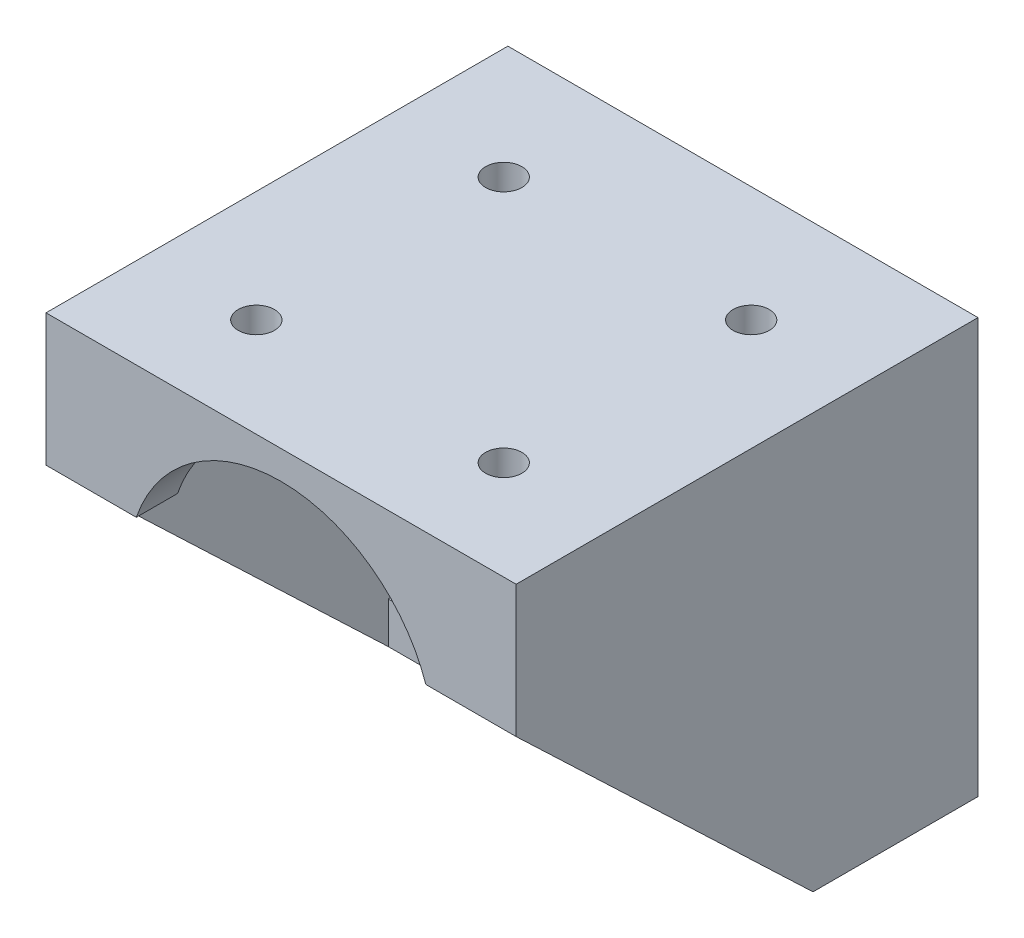
SolidWorks part; units mm, degrees
ref_plane "Plan de face" through (0, 0, 0) normal (0, 0, 1) x (1, 0, 0)
ref_plane "Plan de dessus" through (0, 0, 0) normal (0, 1, 0) x (1, 0, 0)
ref_plane "Plan de droite" through (0, 0, 0) normal (1, 0, 0) x (0, 0, -1)
sketch "Esquisse1" plane through (0, 0, 0) normal (0, 1, 0) x (1, 0, 0)
  line L1 (-23, 23.5) -> (23, 23.5)
  line L2 (-23, 23.5) -> (-23, -23.5)
  line L3 (-23, -23.5) -> (23, -23.5)
  line L4 (23, 23.5) -> (23, -23.5)
  line L5 (-23, 23.5) -> (23, -23.5) construction
  line L6 (-23, -23.5) -> (23, 23.5) construction
  line L7 (-15, 13.5) -> (15, 13.5) construction
  line L8 (-15, 13.5) -> (-15, -16.5) construction
  line L9 (-15, -16.5) -> (15, -16.5) construction
  line L10 (15, 13.5) -> (15, -16.5) construction
  line L11 (-15, 13.5) -> (15, -16.5) construction
  line L12 (-15, -16.5) -> (15, 13.5) construction
  circle A0 centre (-15, 13.5) radius 2.2
  circle A1 centre (-15, -16.5) radius 2.2
  circle A2 centre (15, -16.5) radius 2.2
  circle A3 centre (15, 13.5) radius 2.2
  point P0 (0, 0)
  point P6 (0, -1.5)
  dimension "D6" = 4.4
  dimension "D1" = 46
  dimension "D2" = 47
  dimension "D3" = 7
  dimension "D4" = 8
  dimension "D5" = 30
extrude "Boss.-Extru.1" add sketch "Esquisse1" along normal blind 5
sketch "Esquisse2" plane through (0, 0, 0) normal (0, -1, 0) x (1, 0, 0)
  line L0 (-28.5, -27.5) -> (-28.5, 23.5)
  line L2 (23, -23.5) -> (23, 23.5)
  line L3 (23, 23.5) -> (28.5, 23.5)
  line L6 (-23, -23.5) -> (-23, 23.5)
  line L7 (-23, 23.5) -> (-28.5, 23.5)
  line L9 (23, -23.5) -> (-23, -23.5)
  line L11 (28.5, -27.5) -> (-28.5, -27.5)
  line L13 (28.5, 23.5) -> (28.5, -27.5)
  line L14 (-23, 23.5) -> (23, 23.5) construction
  point P3 (0, -27.5)
  point P8 (0, -23.5)
  dimension "D1" = 57
  dimension "D2" = 51
extrude "Boss.-Extru.2" add sketch "Esquisse2" along normal blind 45.3 from offset 5 offset against normal yes
sketch "Esquisse3" plane through (0, 0, -23.5) normal (0, 0, 1) x (1, 0, 0)
  line L0 (23, 0) -> (-23, 0) construction
  circle A0 centre (0, -10) radius 6.5
  circle A1 centre (0, -17) radius 15.5 construction
  circle A2 centre (7.75, -30.4234) radius 1.6
  circle A3 centre (-7.75, -30.4234) radius 1.6
  circle A4 centre (-15.5, -17) radius 1.6
  circle A5 centre (-7.75, -3.5766) radius 1.6
  circle A6 centre (7.75, -3.5766) radius 1.6
  circle A7 centre (15.5, -17) radius 1.6
  point P22 (0, -17)
  dimension "D2" = 13
  dimension "D4" = 31
  dimension "D5" = 3.2
  dimension "D1" = 10
  dimension "D3" = 17
  dimension "D6" = 6
extrude "Enlèv. mat.-Extru.1" cut sketch "Esquisse3" against normal blind 15
sketch "Esquisse4" plane through (0, 0, -27.5) normal (0, 0, -1) x (-1, 0, 0)
  line L0 (28.5, -40.3) -> (28.5, 5) construction
  line L1 (-28.5, -40.3) -> (28.5, -40.3)
  line L2 (-28.5, -40.3) -> (-28.5, -45.3)
  line L3 (-28.5, -45.3) -> (28.5, -45.3)
  line L4 (28.5, -40.3) -> (28.5, -45.3)
  dimension "D1" = 5
extrude "Boss.-Extru.3" add sketch "Esquisse4" against normal blind 20
sketch "Esquisse7" plane through (0, 5, 0) normal (0, 1, 0) x (1, 0, 0)
  line L0 (28.5, 27.5) -> (28.5, -23.5) construction
  line L1 (-28.5, -23.5) -> (28.5, -23.5)
  line L2 (-28.5, -23.5) -> (-28.5, -28.5)
  line L3 (-28.5, -28.5) -> (28.5, -28.5)
  line L4 (28.5, -23.5) -> (28.5, -28.5)
  dimension "D1" = 5
extrude "Boss.-Extru.4" add sketch "Esquisse7" against normal blind 16
sketch "Esquisse8" plane through (0, 0, 28.5) normal (0, 0, 1) x (1, 0, 0)
  line L0 (-28.5, 5) -> (28.5, 5) construction
  circle A0 centre (0, -17) radius 18.55
  point P4 (0, 5)
  dimension "D2" = 37.1
  dimension "D1" = 22
extrude "Enlèv. mat.-Extru.3" cut sketch "Esquisse8" against normal up to surface (52 mm away) contours A0 up to face at (9.35, -30.4234, -23.5)
sketch "Esquisse10" plane through (28.5, 0, 0) normal (1, 0, 0) x (0, 0, -1)
  line L0 (-23.5, -11) -> (7.5, -40.3)
  line L1 (7.5, -40.3) -> (-23.5, -40.3)
  line L2 (-23.5, -40.3) -> (-23.5, -11)
extrude "Enlèv. mat.-Extru.4" cut sketch "Esquisse10" against normal blind 10
sketch "Esquisse11" plane through (-28.5, 0, 0) normal (-1, 0, 0) x (0, 0, 1)
  line L0 (23.5, -11) -> (-7.5, -40.3)
  line L1 (-7.5, -40.3) -> (23.5, -40.3)
  line L2 (23.5, -40.3) -> (23.5, -11)
extrude "Enlèv. mat.-Extru.5" cut sketch "Esquisse11" against normal blind 10
sketch "Esquisse12" plane through (-28.5, 0, 0) normal (-1, 0, 0) x (0, 0, 1)
  line L0 (-7.5, -45.3) -> (28.5, -11)
  line L1 (28.5, -11) -> (23.5, -11)
  line L2 (23.5, -11) -> (-7.5, -40.3)
  line L3 (-7.5, -40.3) -> (-7.5, -45.3)
extrude "Boss.-Extru.6" add sketch "Esquisse12" along direction (-1, 0, 0) on the side against the normal up to vertex (5.5 mm away)
sketch "Esquisse13" plane through (28.5, 0, 0) normal (1, 0, 0) x (0, 0, -1)
  line L0 (-28.5, -11) -> (7.5, -45.3)
  line L1 (7.5, -45.3) -> (-28.5, -11) construction
  line L2 (7.5, -45.3) -> (7.5, -40.3)
  line L3 (7.5, -40.3) -> (-23.5, -11)
  line L4 (-28.5, -11) -> (-23.5, -11)
extrude "Boss.-Extru.7" add sketch "Esquisse13" against normal up to vertex
sketch "Esquisse14" plane through (0, -45.3, 0) normal (0, -1, 0) x (1, 0, 0)
  line L0 (-28.5, -17.5) -> (28.5, -17.5) construction
  line L1 (-28.5, -7.5) -> (-28.5, -27.5) construction
  line L2 (28.5, -7.5) -> (28.5, -27.5) construction
  line L3 (-14.5, -17.5) -> (14.5, -17.5) construction
  circle A0 centre (-14.5, -17.5) radius 2.2
  circle A1 centre (14.5, -17.5) radius 2.2
  point P10 (0, -17.5)
  dimension "D2" = 4.4
  dimension "D3" = 4.4
  dimension "D1" = 14.5
  dimension "D4" = 14.5
extrude "Enlèv. mat.-Extru.6" cut sketch "Esquisse14" against normal blind 10 contours A1 | A0
